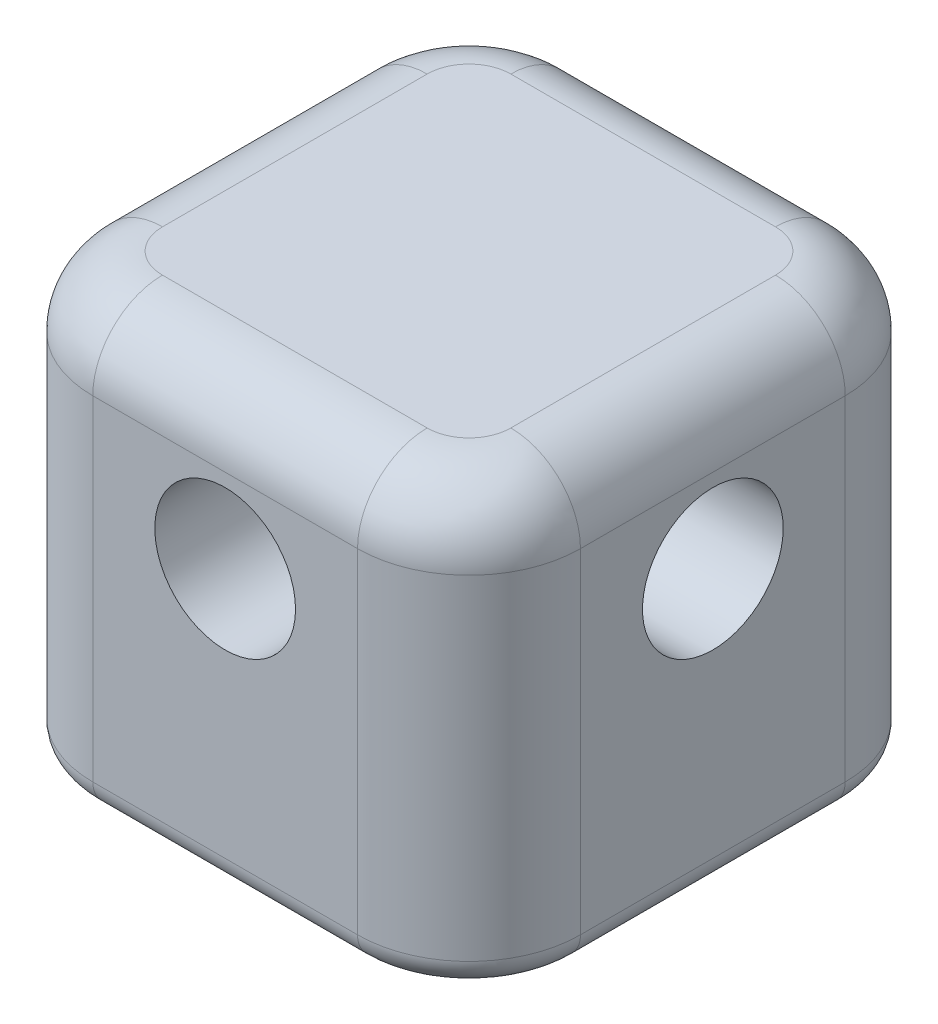
SolidWorks part; units mm, degrees
material "PET"
ref_plane "Спереди" through (0, 0, 0) normal (0, 0, 1) x (1, 0, 0)
ref_plane "Сверху" through (0, 0, 0) normal (0, 1, 0) x (1, 0, 0)
ref_plane "Справа" through (0, 0, 0) normal (1, 0, 0) x (0, 0, -1)
sketch "Эскиз1" plane through (0, 0, 0) normal (0, 1, 0) x (1, 0, 0)
  line L1 (19, 35) -> (-19, 35)
  line L2 (35, 19) -> (35, -19)
  line L3 (19, -35) -> (-19, -35)
  line L4 (-35, 19) -> (-35, -19)
  line L5 (35, 35) -> (-35, -35) construction
  line L6 (35, -35) -> (-35, 35) construction
  circle A0 centre (0, 0) radius 18
  arc A1 (35, -19) -> (19, -35) centre (19, -19) cw
  arc A2 (-19, -35) -> (-35, -19) centre (-19, -19) cw
  arc A3 (-19, 35) -> (-35, 19) centre (-19, 19) ccw
  arc A4 (19, 35) -> (35, 19) centre (19, 19) cw
  dimension "D1" = 36
  dimension "D2" = 16
  dimension "D3" = 70
extrude "Бобышка-Вытянуть1" add sketch "Эскиз1" along normal blind 40
sketch "Эскиз2" plane through (-35, 0, 0) normal (-1, 0, 0) x (0, 0, 1)
  line L0 (19, 40) -> (-19, 0) construction
  circle A0 centre (0, 20) radius 9
  dimension "D1" = 18
extrude "Вырез-Вытянуть2" cut sketch "Эскиз2" against normal through all both and the other way through all contours A0
sketch "Эскиз3" plane through (-35, 0, 0) normal (-1, 0, 0) x (0, 0, 1)
  circle A0 centre (0, 20) radius 10.1
  dimension "D1" = 20.2
extrude "Вырез-Вытянуть3" cut sketch "Эскиз3" against normal blind 15
sketch "Эскиз4" plane through (35, 0, 0) normal (1, 0, 0) x (0, 0, -1)
  circle A1 centre (0, 20) radius 10.1
  circle A2 centre (0, 20) radius 10.1
  dimension "D1" = 0
extrude "Вырез-Вытянуть4" cut sketch "Эскиз4" against normal blind 15
sketch "Эскиз5" plane through (0, 0, 35) normal (0, 0, 1) x (1, 0, 0)
  line L0 (19, 40) -> (-19, 0) construction
  circle A0 centre (0, 20) radius 9
  point P6 (0, 0)
  dimension "D1" = 18
extrude "Вырез-Вытянуть5" cut sketch "Эскиз5" against normal through all both and the other way through all
sketch "Эскиз6" plane through (0, 0, 35) normal (0, 0, 1) x (1, 0, 0)
  circle A0 centre (0, 20) radius 10.1
  dimension "D1" = 20.2
extrude "Вырез-Вытянуть6" cut sketch "Эскиз6" against normal blind 15
sketch "Эскиз7" plane through (0, 0, -35) normal (0, 0, -1) x (-1, 0, 0)
  circle A1 centre (0, 20) radius 10.1
  circle A2 centre (0, 20) radius 10.1
  dimension "D1" = 0
extrude "Вырез-Вытянуть7" cut sketch "Эскиз7" against normal blind 8
sketch "Эскиз9" plane through (0, 40, 0) normal (0, 1, 0) x (1, 0, 0)
  line L5 (35, -19) -> (35, 19)
  line L6 (19, 35) -> (-19, 35)
  line L7 (-35, 19) -> (-35, -19)
  line L12 (-19, -35) -> (19, -35)
  line L13 (35, -19) -> (35, 19)
  line L14 (19, 35) -> (-19, 35)
  line L15 (-35, 19) -> (-35, -19)
  line L16 (-19, -35) -> (19, -35)
  arc A12 (19, -35) -> (35, -19) centre (19, -19) ccw
  arc A13 (35, 19) -> (19, 35) centre (19, 19) ccw
  arc A14 (-19, 35) -> (-35, 19) centre (-19, 19) ccw
  arc A15 (-35, -19) -> (-19, -35) centre (-19, -19) ccw
  arc A16 (19, -35) -> (35, -19) centre (19, -19) ccw
  arc A17 (35, 19) -> (19, 35) centre (19, 19) ccw
  arc A18 (-19, 35) -> (-35, 19) centre (-19, 19) ccw
  arc A19 (-35, -19) -> (-19, -35) centre (-19, -19) ccw
  dimension "D1" = 0
extrude "Бобышка-Вытянуть2" add sketch "Эскиз9" along normal blind 2
fillet "Скругление1" radius 10 8 edges at (0, 42, 35) (-35, 42, 0) (-30.3137, 42, -30.3137) (0, 42, -35) (30.3137, 42, -30.3137) (35, 42, 0) (30.3137, 42, 30.3137) (-30.3137, 42, 30.3137)
sketch "Эскиз10" plane through (0, 0, 0) normal (0, -1, 0) x (1, 0, 0)
  line L7 (19, 35) -> (-19, 35)
  line L12 (-35, 19) -> (-35, -19)
  line L13 (-19, -35) -> (19, -35)
  line L14 (35, -19) -> (35, 19)
  line L15 (19, 35) -> (-19, 35)
  line L16 (-35, 19) -> (-35, -19)
  line L17 (-19, -35) -> (19, -35)
  line L18 (35, -19) -> (35, 19)
  circle A0 centre (0, 0) radius 20.1
  arc A14 (35, 19) -> (19, 35) centre (19, 19) ccw
  arc A15 (-19, 35) -> (-35, 19) centre (-19, 19) ccw
  arc A16 (-35, -19) -> (-19, -35) centre (-19, -19) ccw
  arc A17 (19, -35) -> (35, -19) centre (19, -19) ccw
  arc A18 (35, 19) -> (19, 35) centre (19, 19) ccw
  arc A19 (-19, 35) -> (-35, 19) centre (-19, 19) ccw
  arc A20 (-35, -19) -> (-19, -35) centre (-19, -19) ccw
  arc A21 (19, -35) -> (35, -19) centre (19, -19) ccw
  dimension "D1" = 40.2
  dimension "D2" = 0
extrude "Бобышка-Вытянуть3" add sketch "Эскиз10" along normal blind 20
fillet "Скругление2" radius 4 8 edges at (0, -20, 35) (30.3137, -20, 30.3137) (35, -20, 0) (30.3137, -20, -30.3137) (0, -20, -35) (-30.3137, -20, -30.3137) (-35, -20, 0) (-30.3137, -20, 30.3137)
equation "\"допуск\"= 0.2"
equation "\"D1@Эскиз3\"=\"допуск\"+20"
equation "\"D1@Эскиз6\"=\"допуск\"+20"
equation "\"D1@Эскиз10\"=\"допуск\"+40"
